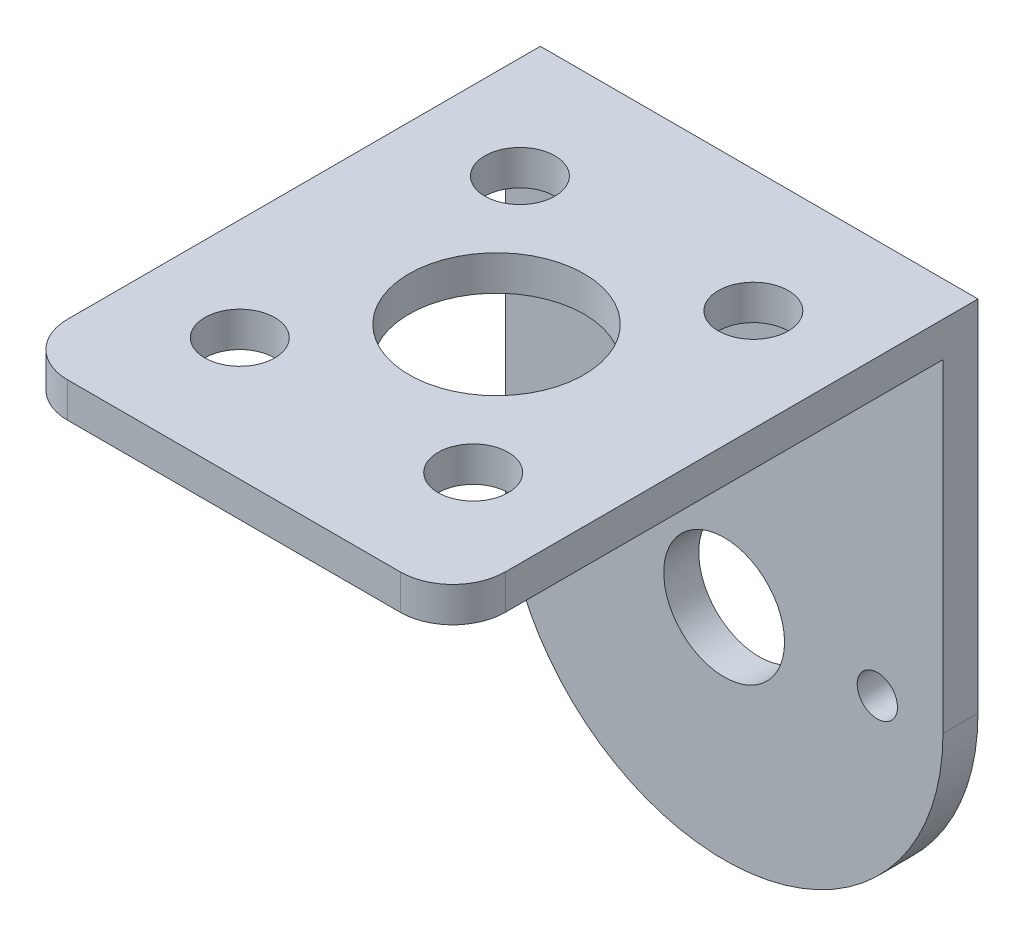
SolidWorks part; units mm, degrees
ref_plane "Plano frontal" through (0, 0, 0) normal (0, 0, 1) x (1, 0, 0)
ref_plane "Plano superior" through (0, 0, 0) normal (0, 1, 0) x (1, 0, 0)
ref_plane "Plano direito" through (0, 0, 0) normal (1, 0, 0) x (0, 0, -1)
sketch "Esboço1" plane through (0, 0, 0) normal (0, 0, 1) x (1, 0, 0)
  line L0 (3.4069, -4) -> (8.7069, -4) construction
  line L2 (12.4569, -4) -> (12.4569, 16.5)
  line L3 (12.4569, 16.5) -> (-12.5431, 16.5)
  line L4 (-12.5431, -4) -> (-12.5431, 16.5)
  line L5 (-3.4931, -4) -> (-8.7931, -4) construction
  arc A1 (-12.5431, -4) -> (12.4569, -4) centre (-0.0431, -4) ccw
  circle A2 centre (-0.0431, -4) radius 3.45
  circle A3 centre (8.7069, -4) radius 1.15
  circle A4 centre (-8.7931, -4) radius 1.15
  point P0 (0, 0)
  dimension "D1" = 6.9
  dimension "D3" = 2.3
  dimension "D5" = 2.3
  dimension "D9" = 16.5
  dimension "D2" = 3.75
  dimension "D4" = 3.75
  dimension "D6" = 4.0002
  dimension "D7" = 25
  dimension "D8" = 20.5
extrude "Ressalto-extrusão2" add sketch "Esboço1" along normal blind 2
sketch "Esboço2" plane through (0, 0, 2) normal (0, 0, 1) x (1, 0, 0)
  line L0 (12.4569, 16.5) -> (-12.5431, 16.5) construction
  line L2 (-12.5431, 16.5) -> (-12.5431, 14.5)
  line L3 (-12.5431, 14.5) -> (12.4569, 14.5)
  line L4 (12.4569, 16.5) -> (12.4569, 14.5)
  line L5 (-12.5431, 16.5) -> (12.4569, 14.5) construction
  line L6 (12.4569, 16.5) -> (-12.5431, 14.5) construction
  line L7 (12.4569, -4) -> (12.4569, 16.5) construction
  line L8 (-12.5431, 16.5) -> (12.4569, 16.5)
  point P0 (-0.0431, 16.5)
  dimension "D1" = 25
  dimension "D2" = 2
  dimension "D3" = 14.5
extrude "Ressalto-extrusão3" add sketch "Esboço2" along normal blind 28
sketch "Esboço3" plane through (0, 14.5, 0) normal (0, -1, 0) x (1, 0, 0)
  line L0 (-12.5431, 0) -> (12.4569, 30) construction
  line L1 (-12.5431, 30) -> (-12.5431, 2) construction
  line L2 (12.4569, 30) -> (-12.5431, 30) construction
  line L3 (-12.5431, 30) -> (12.4569, 2) construction
  line L4 (-19.7052, 15) -> (16.8906, 15) construction
  line L5 (-0.0431, 32.0779) -> (-0.0431, -4.7171) construction
  line L6 (-12.5431, 2) -> (12.4569, 2) construction
  circle A0 centre (-0.0431, 15) radius 5
  circle A1 centre (-6.7098, 7) radius 2
  circle A2 centre (6.6236, 7) radius 2
  circle A3 centre (6.6236, 23) radius 2
  circle A4 centre (-6.7098, 23) radius 2
  dimension "D1" = 10
  dimension "D2" = 4
  dimension "D3" = 8
  dimension "D4" = 5
extrude "Corte-extrusão1" cut sketch "Esboço3" against normal blind 2
fillet "Filete1" radius 3 1 edges at (12.4569, 15.5, 30)
fillet "Filete2" radius 3 1 edges at (-12.5431, 15.5, 30)
